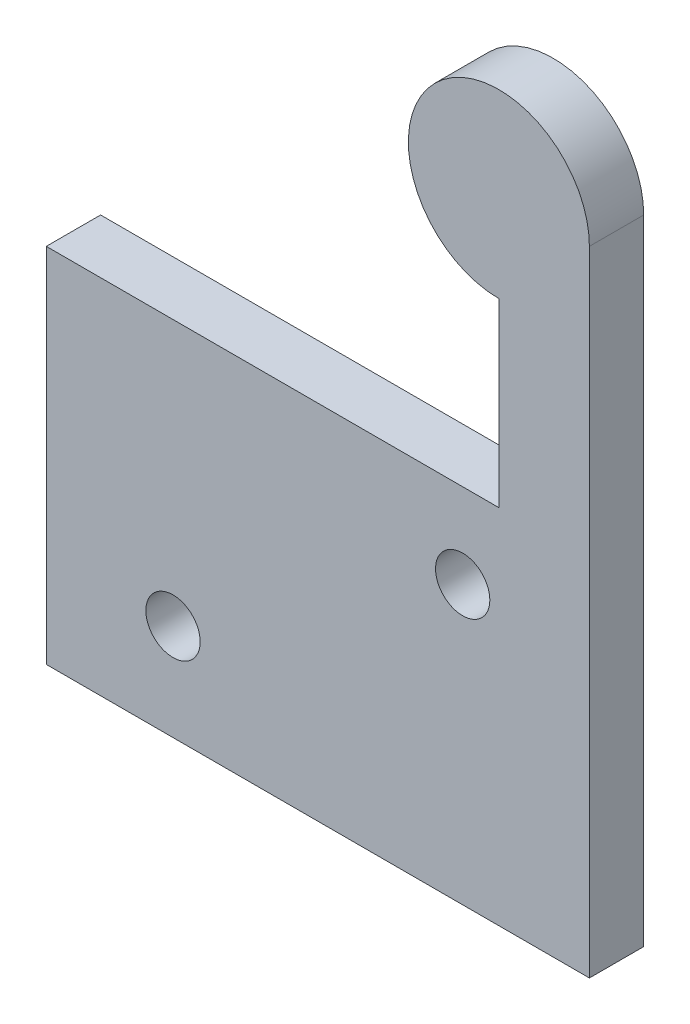
SolidWorks part; units mm, degrees
ref_plane "前视基准面" through (0, 0, 0) normal (0, 0, 1) x (1, 0, 0)
ref_plane "上视基准面" through (0, 0, 0) normal (0, 1, 0) x (1, 0, 0)
ref_plane "右视基准面" through (0, 0, 0) normal (1, 0, 0) x (0, 0, -1)
sketch "草图1" plane through (0, 0, 0) normal (0, 0, 1) x (1, 0, 0)
  line L0 (14.9101, 4.6713) -> (14.9101, 14.6713)
  line L1 (14.9101, 4.6713) -> (-10.0899, 4.6713)
  line L2 (-10.0899, 4.6713) -> (-10.0899, -15.3287)
  line L3 (-10.0899, -15.3287) -> (19.9101, -15.3287)
  line L4 (19.9101, -15.3287) -> (19.9101, 7.3391)
  line L5 (19.9101, 7.3391) -> (19.9101, 19.6713)
  arc A0 (19.9101, 19.6713) -> (14.9101, 14.6713) centre (14.9101, 19.6713) ccw
  dimension "D1" = 5
  dimension "D2" = 25
  dimension "D4" = 20
extrude "凸台-拉伸1" add sketch "草图1" along normal blind 3
sketch "草图2" plane through (0, 0, 3) normal (0, 0, 1) x (1, 0, 0)
  circle A1 centre (12.9101, 0) radius 1.5
  circle A2 centre (-3.0899, -10) radius 1.5
  dimension "D4" = 3
  dimension "D6" = 3
extrude "切除-拉伸2" cut sketch "草图2" against normal blind 6
